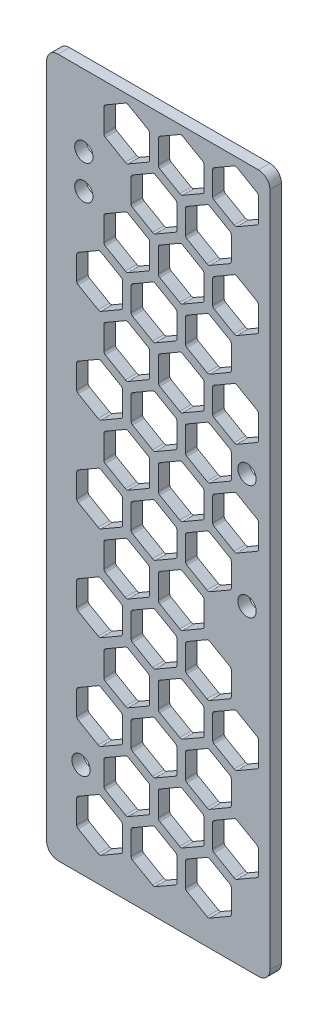
SolidWorks part; units mm, degrees
material "Thornel Mat VMA"
ref_plane "前视基准面" through (0, 0, 0) normal (0, 0, 1) x (1, 0, 0)
ref_plane "上视基准面" through (0, 0, 0) normal (0, 1, 0) x (1, 0, 0)
ref_plane "右视基准面" through (0, 0, 0) normal (1, 0, 0) x (0, 0, -1)
sketch "草图1" plane through (0, 0, 0) normal (0, 0, 1) x (1, 0, 0)
  line L0 (3, -11.5) -> (3, -16.5)
  line L1 (3, -16.5) -> (42, -16.5)
  line L3 (42, 105.5) -> (3, 105.5)
  line L4 (3, 105.5) -> (3, -11.5)
  line L5 (42, 105.5) -> (42, 80.5)
  line L6 (42, 80.5) -> (47, 80.5)
  line L7 (47, 80.5) -> (47, 72.5)
  line L8 (47, 72.5) -> (42, 72.5)
  line L9 (42, 72.5) -> (42, 16.5)
  line L10 (42, 16.5) -> (47, 16.5)
  line L11 (47, 16.5) -> (47, 8.5)
  line L12 (47, 8.5) -> (42, 8.5)
  line L13 (42, 8.5) -> (42, -16.5)
  circle A0 centre (9, 0) radius 1.6
  circle A1 centre (9.5, 93) radius 1.6
  circle A2 centre (9.5, 87) radius 1.6
  circle A3 centre (38, 38.5) radius 1.6
  circle A4 centre (38, 58.5) radius 1.6
  circle A5 centre (38, 58.5) radius 1.6 construction
  dimension "D1" = 25
  dimension "D10" = 20
  dimension "D2" = 8
  dimension "D3" = 5
  dimension "D4" = 8
  dimension "D5" = 5
  dimension "D6" = 25
  dimension "D8" = 5
extrude "凸台-拉伸1" add sketch "草图1" along normal blind 2
sketch "草图3" plane through (0, 0, 2) normal (0, 0, 1) x (1, 0, 0)
  line L0 (42, 80.5) -> (42, 72.5)
  line L1 (42, 72.5) -> (55.038, 72.5)
  line L2 (55.038, 72.5) -> (55.038, 80.5)
  line L3 (55.038, 80.5) -> (42, 80.5)
  line L4 (42, 16.5) -> (42, 8.5)
  line L5 (42, 8.5) -> (56.361, 8.5)
  line L6 (56.361, 8.5) -> (56.361, 16.5)
  line L7 (56.361, 16.5) -> (42, 16.5)
extrude "切除-拉伸2" cut sketch "草图3" against normal through all
sketch "草图4" plane through (0, 0, 2) normal (0, 0, 1) x (1, 0, 0)
  line L0 (42, -16.5) -> (42, 105.5) construction
  line L1 (35.75, 103.9745) -> (32.25, 101.9537)
  line L2 (32, 101.5207) -> (32, 97.4793)
  line L3 (32.25, 97.0463) -> (35.75, 95.0255)
  line L4 (36.25, 95.0255) -> (39.75, 97.0463)
  line L5 (40, 97.4793) -> (40, 101.5207)
  line L6 (39.75, 101.9537) -> (36.25, 103.9745)
  line L7 (42, 105.5) -> (3, 105.5) construction
  line L44 (26.25, 103.9745) -> (22.75, 101.9537)
  line L51 (22.5, 101.5207) -> (22.5, 97.4793)
  line L52 (22.75, 97.0463) -> (26.25, 95.0255)
  line L53 (26.75, 95.0255) -> (30.25, 97.0463)
  line L54 (30.5, 97.4793) -> (30.5, 101.5207)
  line L55 (30.25, 101.9537) -> (26.75, 103.9745)
  line L56 (16.75, 103.9745) -> (13.25, 101.9537)
  line L57 (13, 101.5207) -> (13, 97.4793)
  line L58 (13.25, 97.0463) -> (16.75, 95.0255)
  line L59 (17.25, 95.0255) -> (20.75, 97.0463)
  line L60 (21, 97.4793) -> (21, 101.5207)
  line L61 (20.75, 101.9537) -> (17.25, 103.9745)
  line L62 (21.5, 95.7472) -> (18, 93.7265)
  line L63 (31, 95.7472) -> (27.5, 93.7265)
  line L64 (27.25, 93.2935) -> (27.25, 89.252)
  line L65 (27.5, 88.819) -> (31, 86.7983)
  line L66 (31.5, 86.7983) -> (35, 88.819)
  line L67 (35.25, 89.252) -> (35.25, 93.2935)
  line L68 (35, 93.7265) -> (31.5, 95.7472)
  line L69 (17.75, 93.2935) -> (17.75, 89.252)
  line L70 (18, 88.819) -> (21.5, 86.7983)
  line L71 (22, 86.7983) -> (25.5, 88.819)
  line L72 (25.75, 89.252) -> (25.75, 93.2935)
  line L73 (25.5, 93.7265) -> (22, 95.7472)
  line L74 (26.25, 87.52) -> (22.75, 85.4993)
  line L75 (35.75, 87.52) -> (32.25, 85.4993)
  line L76 (32, 85.0662) -> (32, 81.0248)
  line L77 (32.25, 80.5918) -> (35.75, 78.5711)
  line L78 (36.25, 78.5711) -> (39.75, 80.5918)
  line L79 (40, 81.0248) -> (40, 85.0662)
  line L80 (39.75, 85.4993) -> (36.25, 87.52)
  line L81 (22.5, 85.0662) -> (22.5, 81.0248)
  line L82 (22.75, 80.5918) -> (26.25, 78.5711)
  line L83 (26.75, 78.5711) -> (30.25, 80.5918)
  line L84 (30.5, 81.0248) -> (30.5, 85.0662)
  line L85 (30.25, 85.4993) -> (26.75, 87.52)
  line L86 (16.75, 87.52) -> (13.25, 85.4993)
  line L87 (13, 85.0662) -> (13, 81.0248)
  line L88 (13.25, 80.5918) -> (16.75, 78.5711)
  line L89 (17.25, 78.5711) -> (20.75, 80.5918)
  line L90 (21, 81.0248) -> (21, 85.0662)
  line L91 (20.75, 85.4993) -> (17.25, 87.52)
  line L92 (21.5, 79.2927) -> (18, 77.272)
  line L93 (31, 79.2927) -> (27.5, 77.272)
  line L94 (27.25, 76.839) -> (27.25, 72.7976)
  line L95 (27.5, 72.3645) -> (31, 70.3438)
  line L96 (31.5, 70.3438) -> (35, 72.3645)
  line L97 (35.25, 72.7976) -> (35.25, 76.839)
  line L98 (35, 77.272) -> (31.5, 79.2927)
  line L99 (17.75, 76.839) -> (17.75, 72.7976)
  line L100 (18, 72.3645) -> (21.5, 70.3438)
  line L101 (22, 70.3438) -> (25.5, 72.3645)
  line L102 (25.75, 72.7976) -> (25.75, 76.839)
  line L103 (25.5, 77.272) -> (22, 79.2927)
  line L104 (12, 79.2927) -> (8.5, 77.272)
  line L105 (8.25, 76.839) -> (8.25, 72.7976)
  line L106 (8.5, 72.3645) -> (12, 70.3438)
  line L107 (12.5, 70.3438) -> (16, 72.3645)
  line L108 (16.25, 72.7976) -> (16.25, 76.839)
  line L109 (16, 77.272) -> (12.5, 79.2927)
  line L110 (16.75, 71.0655) -> (13.25, 69.0448)
  line L111 (13, 68.6118) -> (13, 64.5703)
  line L112 (13.25, 64.1373) -> (16.75, 62.1166)
  line L113 (17.25, 62.1166) -> (20.75, 64.1373)
  line L114 (21, 64.5703) -> (21, 68.6118)
  line L115 (20.75, 69.0448) -> (17.25, 71.0655)
  line L116 (26.25, 71.0655) -> (22.75, 69.0448)
  line L117 (22.5, 68.6118) -> (22.5, 64.5703)
  line L118 (22.75, 64.1373) -> (26.25, 62.1166)
  line L119 (26.75, 62.1166) -> (30.25, 64.1373)
  line L120 (30.5, 64.5703) -> (30.5, 68.6118)
  line L121 (30.25, 69.0448) -> (26.75, 71.0655)
  line L122 (35.75, 71.0655) -> (32.25, 69.0448)
  line L123 (32, 68.6118) -> (32, 64.5703)
  line L124 (32.25, 64.1373) -> (35.75, 62.1166)
  line L125 (36.25, 62.1166) -> (39.75, 64.1373)
  line L126 (40, 64.5703) -> (40, 68.6118)
  line L127 (39.75, 69.0448) -> (36.25, 71.0655)
  line L128 (31, 62.8383) -> (27.5, 60.8175)
  line L129 (27.25, 60.3845) -> (27.25, 56.3431)
  line L130 (27.5, 55.9101) -> (31, 53.8893)
  line L131 (31.5, 53.8893) -> (35, 55.9101)
  line L132 (35.25, 56.3431) -> (35.25, 60.3845)
  line L133 (35, 60.8175) -> (31.5, 62.8383)
  line L134 (21.5, 62.8383) -> (18, 60.8175)
  line L135 (17.75, 60.3845) -> (17.75, 56.3431)
  line L136 (18, 55.9101) -> (21.5, 53.8893)
  line L137 (22, 53.8893) -> (25.5, 55.9101)
  line L138 (25.75, 56.3431) -> (25.75, 60.3845)
  line L139 (25.5, 60.8175) -> (22, 62.8383)
  line L140 (12, 62.8383) -> (8.5, 60.8175)
  line L141 (8.25, 60.3845) -> (8.25, 56.3431)
  line L142 (8.5, 55.9101) -> (12, 53.8893)
  line L143 (12.5, 53.8893) -> (16, 55.9101)
  line L144 (16.25, 56.3431) -> (16.25, 60.3845)
  line L145 (16, 60.8175) -> (12.5, 62.8383)
  line L146 (16.75, 54.611) -> (13.25, 52.5903)
  line L147 (13, 52.1573) -> (13, 48.1158)
  line L148 (13.25, 47.6828) -> (16.75, 45.6621)
  line L149 (17.25, 45.6621) -> (20.75, 47.6828)
  line L150 (21, 48.1158) -> (21, 52.1573)
  line L151 (20.75, 52.5903) -> (17.25, 54.611)
  line L152 (26.25, 54.611) -> (22.75, 52.5903)
  line L153 (22.5, 52.1573) -> (22.5, 48.1158)
  line L154 (22.75, 47.6828) -> (26.25, 45.6621)
  line L155 (26.75, 45.6621) -> (30.25, 47.6828)
  line L156 (30.5, 48.1158) -> (30.5, 52.1573)
  line L157 (30.25, 52.5903) -> (26.75, 54.611)
  line L158 (35.75, 54.611) -> (32.25, 52.5903)
  line L159 (32, 52.1573) -> (32, 48.1158)
  line L160 (32.25, 47.6828) -> (35.75, 45.6621)
  line L161 (36.25, 45.6621) -> (39.75, 47.6828)
  line L162 (40, 48.1158) -> (40, 52.1573)
  line L163 (39.75, 52.5903) -> (36.25, 54.611)
  line L164 (31, 46.3838) -> (27.5, 44.363)
  line L165 (27.25, 43.93) -> (27.25, 39.8886)
  line L166 (27.5, 39.4556) -> (31, 37.4348)
  line L167 (31.5, 37.4348) -> (35, 39.4556)
  line L168 (35.25, 39.8886) -> (35.25, 43.93)
  line L169 (35, 44.363) -> (31.5, 46.3838)
  line L170 (21.5, 46.3838) -> (18, 44.363)
  line L171 (17.75, 43.93) -> (17.75, 39.8886)
  line L172 (18, 39.4556) -> (21.5, 37.4348)
  line L173 (22, 37.4348) -> (25.5, 39.4556)
  line L174 (25.75, 39.8886) -> (25.75, 43.93)
  line L175 (25.5, 44.363) -> (22, 46.3838)
  line L176 (12, 46.3838) -> (8.5, 44.363)
  line L177 (8.25, 43.93) -> (8.25, 39.8886)
  line L178 (8.5, 39.4556) -> (12, 37.4348)
  line L179 (12.5, 37.4348) -> (16, 39.4556)
  line L180 (16.25, 39.8886) -> (16.25, 43.93)
  line L181 (16, 44.363) -> (12.5, 46.3838)
  line L182 (16.75, 38.1565) -> (13.25, 36.1358)
  line L183 (13, 35.7028) -> (13, 31.6613)
  line L184 (13.25, 31.2283) -> (16.75, 29.2076)
  line L185 (17.25, 29.2076) -> (20.75, 31.2283)
  line L186 (21, 31.6613) -> (21, 35.7028)
  line L187 (20.75, 36.1358) -> (17.25, 38.1565)
  line L188 (26.25, 38.1565) -> (22.75, 36.1358)
  line L189 (22.5, 35.7028) -> (22.5, 31.6613)
  line L190 (22.75, 31.2283) -> (26.25, 29.2076)
  line L191 (26.75, 29.2076) -> (30.25, 31.2283)
  line L192 (30.5, 31.6613) -> (30.5, 35.7028)
  line L193 (30.25, 36.1358) -> (26.75, 38.1565)
  line L200 (31, 29.9293) -> (27.5, 27.9086)
  line L201 (27.25, 27.4756) -> (27.25, 23.4341)
  line L202 (27.5, 23.0011) -> (31, 20.9804)
  line L203 (31.5, 20.9804) -> (35, 23.0011)
  line L204 (35.25, 23.4341) -> (35.25, 27.4756)
  line L205 (35, 27.9086) -> (31.5, 29.9293)
  line L206 (21.5, 29.9293) -> (18, 27.9086)
  line L207 (17.75, 27.4756) -> (17.75, 23.4341)
  line L208 (18, 23.0011) -> (21.5, 20.9804)
  line L209 (22, 20.9804) -> (25.5, 23.0011)
  line L210 (25.75, 23.4341) -> (25.75, 27.4756)
  line L211 (25.5, 27.9086) -> (22, 29.9293)
  line L212 (12, 29.9293) -> (8.5, 27.9086)
  line L213 (8.25, 27.4756) -> (8.25, 23.4341)
  line L214 (8.5, 23.0011) -> (12, 20.9804)
  line L215 (12.5, 20.9804) -> (16, 23.0011)
  line L216 (16.25, 23.4341) -> (16.25, 27.4756)
  line L217 (16, 27.9086) -> (12.5, 29.9293)
  line L218 (16.75, 21.7021) -> (13.25, 19.6813)
  line L219 (13, 19.2483) -> (13, 15.2069)
  line L220 (13.25, 14.7738) -> (16.75, 12.7531)
  line L221 (17.25, 12.7531) -> (20.75, 14.7738)
  line L222 (21, 15.2069) -> (21, 19.2483)
  line L223 (20.75, 19.6813) -> (17.25, 21.7021)
  line L224 (26.25, 21.7021) -> (22.75, 19.6813)
  line L225 (22.5, 19.2483) -> (22.5, 15.2069)
  line L226 (22.75, 14.7738) -> (26.25, 12.7531)
  line L227 (26.75, 12.7531) -> (30.25, 14.7738)
  line L228 (30.5, 15.2069) -> (30.5, 19.2483)
  line L229 (30.25, 19.6813) -> (26.75, 21.7021)
  line L230 (35.75, 21.7021) -> (32.25, 19.6813)
  line L231 (32, 19.2483) -> (32, 15.2069)
  line L232 (32.25, 14.7738) -> (35.75, 12.7531)
  line L233 (36.25, 12.7531) -> (39.75, 14.7738)
  line L234 (40, 15.2069) -> (40, 19.2483)
  line L235 (39.75, 19.6813) -> (36.25, 21.7021)
  line L236 (31, 13.4748) -> (27.5, 11.4541)
  line L237 (27.25, 11.0211) -> (27.25, 6.9796)
  line L238 (27.5, 6.5466) -> (31, 4.5259)
  line L239 (31.5, 4.5259) -> (35, 6.5466)
  line L240 (35.25, 6.9796) -> (35.25, 11.0211)
  line L241 (35, 11.4541) -> (31.5, 13.4748)
  line L242 (21.5, 13.4748) -> (18, 11.4541)
  line L243 (17.75, 11.0211) -> (17.75, 6.9796)
  line L244 (18, 6.5466) -> (21.5, 4.5259)
  line L245 (22, 4.5259) -> (25.5, 6.5466)
  line L246 (25.75, 6.9796) -> (25.75, 11.0211)
  line L247 (25.5, 11.4541) -> (22, 13.4748)
  line L248 (12, 13.4748) -> (8.5, 11.4541)
  line L249 (8.25, 11.0211) -> (8.25, 6.9796)
  line L250 (8.5, 6.5466) -> (12, 4.5259)
  line L251 (12.5, 4.5259) -> (16, 6.5466)
  line L252 (16.25, 6.9796) -> (16.25, 11.0211)
  line L253 (16, 11.4541) -> (12.5, 13.4748)
  line L254 (16.75, 5.2476) -> (13.25, 3.2268)
  line L255 (13, 2.7938) -> (13, -1.2476)
  line L256 (13.25, -1.6806) -> (16.75, -3.7014)
  line L257 (17.25, -3.7014) -> (20.75, -1.6806)
  line L258 (21, -1.2476) -> (21, 2.7938)
  line L259 (20.75, 3.2268) -> (17.25, 5.2476)
  line L260 (26.25, 5.2476) -> (22.75, 3.2268)
  line L261 (22.5, 2.7938) -> (22.5, -1.2476)
  line L262 (22.75, -1.6806) -> (26.25, -3.7014)
  line L263 (26.75, -3.7014) -> (30.25, -1.6806)
  line L264 (30.5, -1.2476) -> (30.5, 2.7938)
  line L265 (30.25, 3.2268) -> (26.75, 5.2476)
  line L266 (35.75, 5.2476) -> (32.25, 3.2268)
  line L267 (32, 2.7938) -> (32, -1.2476)
  line L268 (32.25, -1.6806) -> (35.75, -3.7014)
  line L269 (36.25, -3.7014) -> (39.75, -1.6806)
  line L270 (40, -1.2476) -> (40, 2.7938)
  line L271 (39.75, 3.2268) -> (36.25, 5.2476)
  line L272 (31, -2.9797) -> (27.5, -5.0004)
  line L273 (27.25, -5.4334) -> (27.25, -9.4749)
  line L274 (27.5, -9.9079) -> (31, -11.9286)
  line L275 (31.5, -11.9286) -> (35, -9.9079)
  line L276 (35.25, -9.4749) -> (35.25, -5.4334)
  line L277 (35, -5.0004) -> (31.5, -2.9797)
  line L278 (21.5, -2.9797) -> (18, -5.0004)
  line L279 (17.75, -5.4334) -> (17.75, -9.4749)
  line L280 (18, -9.9079) -> (21.5, -11.9286)
  line L281 (22, -11.9286) -> (25.5, -9.9079)
  line L282 (25.75, -9.4749) -> (25.75, -5.4334)
  line L283 (25.5, -5.0004) -> (22, -2.9797)
  line L284 (12, -2.9797) -> (8.5, -5.0004)
  line L285 (8.25, -5.4334) -> (8.25, -9.4749)
  line L286 (8.5, -9.9079) -> (12, -11.9286)
  line L287 (12.5, -11.9286) -> (16, -9.9079)
  line L288 (16.25, -9.4749) -> (16.25, -5.4334)
  line L289 (16, -5.0004) -> (12.5, -2.9797)
  line L290 (35.75, 38.1565) -> (32.25, 36.1358) [skipped]
  line L291 (32, 35.7028) -> (32, 31.6613) [skipped]
  line L292 (32.25, 31.2283) -> (35.75, 29.2076) [skipped]
  line L293 (36.25, 29.2076) -> (39.75, 31.2283) [skipped]
  line L294 (40, 31.6613) -> (40, 35.7028) [skipped]
  line L295 (39.75, 36.1358) -> (36.25, 38.1565) [skipped]
  circle A0 centre (36, 99.5) radius 4 construction
  arc A1 (32.25, 101.9537) -> (32, 101.5207) centre (32.5, 101.5207) ccw
  arc A2 (32, 97.4793) -> (32.25, 97.0463) centre (32.5, 97.4793) ccw
  arc A3 (35.75, 95.0255) -> (36.25, 95.0255) centre (36, 95.4585) ccw
  arc A4 (39.75, 97.0463) -> (40, 97.4793) centre (39.5, 97.4793) ccw
  arc A5 (40, 101.5207) -> (39.75, 101.9537) centre (39.5, 101.5207) ccw
  arc A6 (35.75, 103.9745) -> (36.25, 103.9745) centre (36, 103.5415) cw
  arc A45 (22.75, 101.9537) -> (22.5, 101.5207) centre (23, 101.5207) ccw
  arc A46 (22.5, 97.4793) -> (22.75, 97.0463) centre (23, 97.4793) ccw
  arc A47 (26.25, 95.0255) -> (26.75, 95.0255) centre (26.5, 95.4585) ccw
  arc A48 (30.25, 97.0463) -> (30.5, 97.4793) centre (30, 97.4793) ccw
  arc A49 (30.5, 101.5207) -> (30.25, 101.9537) centre (30, 101.5207) ccw
  arc A50 (26.25, 103.9745) -> (26.75, 103.9745) centre (26.5, 103.5415) cw
  circle A51 centre (26.5, 99.5) radius 4 construction
  arc A52 (13.25, 101.9537) -> (13, 101.5207) centre (13.5, 101.5207) ccw
  arc A53 (13, 97.4793) -> (13.25, 97.0463) centre (13.5, 97.4793) ccw
  arc A54 (16.75, 95.0255) -> (17.25, 95.0255) centre (17, 95.4585) ccw
  arc A55 (20.75, 97.0463) -> (21, 97.4793) centre (20.5, 97.4793) ccw
  arc A56 (21, 101.5207) -> (20.75, 101.9537) centre (20.5, 101.5207) ccw
  arc A57 (16.75, 103.9745) -> (17.25, 103.9745) centre (17, 103.5415) cw
  circle A58 centre (17, 99.5) radius 4 construction
  circle A59 centre (31.25, 91.2728) radius 4 construction
  arc A60 (27.5, 93.7265) -> (27.25, 93.2935) centre (27.75, 93.2935) ccw
  arc A61 (27.25, 89.252) -> (27.5, 88.819) centre (27.75, 89.252) ccw
  arc A62 (31, 86.7983) -> (31.5, 86.7983) centre (31.25, 87.2313) ccw
  arc A63 (35, 88.819) -> (35.25, 89.252) centre (34.75, 89.252) ccw
  arc A64 (35.25, 93.2935) -> (35, 93.7265) centre (34.75, 93.2935) ccw
  arc A65 (31, 95.7472) -> (31.5, 95.7472) centre (31.25, 95.3142) cw
  arc A66 (21.5, 95.7472) -> (22, 95.7472) centre (21.75, 95.3142) cw
  arc A67 (18, 93.7265) -> (17.75, 93.2935) centre (18.25, 93.2935) ccw
  arc A68 (17.75, 89.252) -> (18, 88.819) centre (18.25, 89.252) ccw
  arc A69 (21.5, 86.7983) -> (22, 86.7983) centre (21.75, 87.2313) ccw
  arc A70 (25.5, 88.819) -> (25.75, 89.252) centre (25.25, 89.252) ccw
  arc A71 (25.75, 93.2935) -> (25.5, 93.7265) centre (25.25, 93.2935) ccw
  circle A72 centre (36, 83.0455) radius 4 construction
  arc A73 (32.25, 85.4993) -> (32, 85.0662) centre (32.5, 85.0662) ccw
  arc A74 (32, 81.0248) -> (32.25, 80.5918) centre (32.5, 81.0248) ccw
  arc A75 (35.75, 78.5711) -> (36.25, 78.5711) centre (36, 79.0041) ccw
  arc A76 (39.75, 80.5918) -> (40, 81.0248) centre (39.5, 81.0248) ccw
  arc A77 (40, 85.0662) -> (39.75, 85.4993) centre (39.5, 85.0662) ccw
  arc A78 (35.75, 87.52) -> (36.25, 87.52) centre (36, 87.087) cw
  arc A79 (26.25, 87.52) -> (26.75, 87.52) centre (26.5, 87.087) cw
  arc A80 (22.75, 85.4993) -> (22.5, 85.0662) centre (23, 85.0662) ccw
  arc A81 (22.5, 81.0248) -> (22.75, 80.5918) centre (23, 81.0248) ccw
  arc A82 (26.25, 78.5711) -> (26.75, 78.5711) centre (26.5, 79.0041) ccw
  arc A83 (30.25, 80.5918) -> (30.5, 81.0248) centre (30, 81.0248) ccw
  arc A84 (30.5, 85.0662) -> (30.25, 85.4993) centre (30, 85.0662) ccw
  arc A85 (16.75, 87.52) -> (17.25, 87.52) centre (17, 87.087) cw
  arc A86 (13.25, 85.4993) -> (13, 85.0662) centre (13.5, 85.0662) ccw
  arc A87 (13, 81.0248) -> (13.25, 80.5918) centre (13.5, 81.0248) ccw
  arc A88 (16.75, 78.5711) -> (17.25, 78.5711) centre (17, 79.0041) ccw
  arc A89 (20.75, 80.5918) -> (21, 81.0248) centre (20.5, 81.0248) ccw
  arc A90 (21, 85.0662) -> (20.75, 85.4993) centre (20.5, 85.0662) ccw
  circle A91 centre (31.25, 74.8183) radius 4 construction
  arc A92 (27.5, 77.272) -> (27.25, 76.839) centre (27.75, 76.839) ccw
  arc A93 (27.25, 72.7976) -> (27.5, 72.3645) centre (27.75, 72.7976) ccw
  arc A94 (31, 70.3438) -> (31.5, 70.3438) centre (31.25, 70.7768) ccw
  arc A95 (35, 72.3645) -> (35.25, 72.7976) centre (34.75, 72.7976) ccw
  arc A96 (35.25, 76.839) -> (35, 77.272) centre (34.75, 76.839) ccw
  arc A97 (31, 79.2927) -> (31.5, 79.2927) centre (31.25, 78.8597) cw
  arc A98 (21.5, 79.2927) -> (22, 79.2927) centre (21.75, 78.8597) cw
  arc A99 (18, 77.272) -> (17.75, 76.839) centre (18.25, 76.839) ccw
  arc A100 (17.75, 72.7976) -> (18, 72.3645) centre (18.25, 72.7976) ccw
  arc A101 (21.5, 70.3438) -> (22, 70.3438) centre (21.75, 70.7768) ccw
  arc A102 (25.5, 72.3645) -> (25.75, 72.7976) centre (25.25, 72.7976) ccw
  arc A103 (25.75, 76.839) -> (25.5, 77.272) centre (25.25, 76.839) ccw
  arc A104 (12, 79.2927) -> (12.5, 79.2927) centre (12.25, 78.8597) cw
  arc A105 (8.5, 77.272) -> (8.25, 76.839) centre (8.75, 76.839) ccw
  arc A106 (8.25, 72.7976) -> (8.5, 72.3645) centre (8.75, 72.7976) ccw
  arc A107 (12, 70.3438) -> (12.5, 70.3438) centre (12.25, 70.7768) ccw
  arc A108 (16, 72.3645) -> (16.25, 72.7976) centre (15.75, 72.7976) ccw
  arc A109 (16.25, 76.839) -> (16, 77.272) centre (15.75, 76.839) ccw
  arc A110 (13.25, 69.0448) -> (13, 68.6118) centre (13.5, 68.6118) ccw
  arc A111 (13, 64.5703) -> (13.25, 64.1373) centre (13.5, 64.5703) ccw
  arc A112 (16.75, 62.1166) -> (17.25, 62.1166) centre (17, 62.5496) ccw
  arc A113 (20.75, 64.1373) -> (21, 64.5703) centre (20.5, 64.5703) ccw
  arc A114 (21, 68.6118) -> (20.75, 69.0448) centre (20.5, 68.6118) ccw
  arc A115 (16.75, 71.0655) -> (17.25, 71.0655) centre (17, 70.6325) cw
  arc A116 (22.75, 69.0448) -> (22.5, 68.6118) centre (23, 68.6118) ccw
  arc A117 (22.5, 64.5703) -> (22.75, 64.1373) centre (23, 64.5703) ccw
  arc A118 (26.25, 62.1166) -> (26.75, 62.1166) centre (26.5, 62.5496) ccw
  arc A119 (30.25, 64.1373) -> (30.5, 64.5703) centre (30, 64.5703) ccw
  arc A120 (30.5, 68.6118) -> (30.25, 69.0448) centre (30, 68.6118) ccw
  arc A121 (26.25, 71.0655) -> (26.75, 71.0655) centre (26.5, 70.6325) cw
  arc A122 (35.75, 71.0655) -> (36.25, 71.0655) centre (36, 70.6325) cw
  arc A123 (32.25, 69.0448) -> (32, 68.6118) centre (32.5, 68.6118) ccw
  arc A124 (32, 64.5703) -> (32.25, 64.1373) centre (32.5, 64.5703) ccw
  arc A125 (35.75, 62.1166) -> (36.25, 62.1166) centre (36, 62.5496) ccw
  arc A126 (39.75, 64.1373) -> (40, 64.5703) centre (39.5, 64.5703) ccw
  arc A127 (40, 68.6118) -> (39.75, 69.0448) centre (39.5, 68.6118) ccw
  arc A128 (31, 62.8383) -> (31.5, 62.8383) centre (31.25, 62.4052) cw
  arc A129 (27.5, 60.8175) -> (27.25, 60.3845) centre (27.75, 60.3845) ccw
  arc A130 (27.25, 56.3431) -> (27.5, 55.9101) centre (27.75, 56.3431) ccw
  arc A131 (31, 53.8893) -> (31.5, 53.8893) centre (31.25, 54.3223) ccw
  arc A132 (35, 55.9101) -> (35.25, 56.3431) centre (34.75, 56.3431) ccw
  arc A133 (35.25, 60.3845) -> (35, 60.8175) centre (34.75, 60.3845) ccw
  arc A134 (18, 60.8175) -> (17.75, 60.3845) centre (18.25, 60.3845) ccw
  arc A135 (17.75, 56.3431) -> (18, 55.9101) centre (18.25, 56.3431) ccw
  arc A136 (21.5, 53.8893) -> (22, 53.8893) centre (21.75, 54.3223) ccw
  arc A137 (25.5, 55.9101) -> (25.75, 56.3431) centre (25.25, 56.3431) ccw
  arc A138 (25.75, 60.3845) -> (25.5, 60.8175) centre (25.25, 60.3845) ccw
  arc A139 (21.5, 62.8383) -> (22, 62.8383) centre (21.75, 62.4052) cw
  arc A140 (8.5, 60.8175) -> (8.25, 60.3845) centre (8.75, 60.3845) ccw
  arc A141 (8.25, 56.3431) -> (8.5, 55.9101) centre (8.75, 56.3431) ccw
  arc A142 (12, 53.8893) -> (12.5, 53.8893) centre (12.25, 54.3223) ccw
  arc A143 (16, 55.9101) -> (16.25, 56.3431) centre (15.75, 56.3431) ccw
  arc A144 (16.25, 60.3845) -> (16, 60.8175) centre (15.75, 60.3845) ccw
  arc A145 (12, 62.8383) -> (12.5, 62.8383) centre (12.25, 62.4052) cw
  arc A146 (13.25, 52.5903) -> (13, 52.1573) centre (13.5, 52.1573) ccw
  arc A147 (13, 48.1158) -> (13.25, 47.6828) centre (13.5, 48.1158) ccw
  arc A148 (16.75, 45.6621) -> (17.25, 45.6621) centre (17, 46.0951) ccw
  arc A149 (20.75, 47.6828) -> (21, 48.1158) centre (20.5, 48.1158) ccw
  arc A150 (21, 52.1573) -> (20.75, 52.5903) centre (20.5, 52.1573) ccw
  arc A151 (16.75, 54.611) -> (17.25, 54.611) centre (17, 54.178) cw
  arc A152 (22.75, 52.5903) -> (22.5, 52.1573) centre (23, 52.1573) ccw
  arc A153 (22.5, 48.1158) -> (22.75, 47.6828) centre (23, 48.1158) ccw
  arc A154 (26.25, 45.6621) -> (26.75, 45.6621) centre (26.5, 46.0951) ccw
  arc A155 (30.25, 47.6828) -> (30.5, 48.1158) centre (30, 48.1158) ccw
  arc A156 (30.5, 52.1573) -> (30.25, 52.5903) centre (30, 52.1573) ccw
  arc A157 (26.25, 54.611) -> (26.75, 54.611) centre (26.5, 54.178) cw
  arc A158 (32.25, 52.5903) -> (32, 52.1573) centre (32.5, 52.1573) ccw
  arc A159 (32, 48.1158) -> (32.25, 47.6828) centre (32.5, 48.1158) ccw
  arc A160 (35.75, 45.6621) -> (36.25, 45.6621) centre (36, 46.0951) ccw
  arc A161 (39.75, 47.6828) -> (40, 48.1158) centre (39.5, 48.1158) ccw
  arc A162 (40, 52.1573) -> (39.75, 52.5903) centre (39.5, 52.1573) ccw
  arc A163 (35.75, 54.611) -> (36.25, 54.611) centre (36, 54.178) cw
  arc A164 (27.5, 44.363) -> (27.25, 43.93) centre (27.75, 43.93) ccw
  arc A165 (27.25, 39.8886) -> (27.5, 39.4556) centre (27.75, 39.8886) ccw
  arc A166 (31, 37.4348) -> (31.5, 37.4348) centre (31.25, 37.8679) ccw
  arc A167 (35, 39.4556) -> (35.25, 39.8886) centre (34.75, 39.8886) ccw
  arc A168 (35.25, 43.93) -> (35, 44.363) centre (34.75, 43.93) ccw
  arc A169 (31, 46.3838) -> (31.5, 46.3838) centre (31.25, 45.9508) cw
  arc A170 (18, 44.363) -> (17.75, 43.93) centre (18.25, 43.93) ccw
  arc A171 (17.75, 39.8886) -> (18, 39.4556) centre (18.25, 39.8886) ccw
  arc A172 (21.5, 37.4348) -> (22, 37.4348) centre (21.75, 37.8679) ccw
  arc A173 (25.5, 39.4556) -> (25.75, 39.8886) centre (25.25, 39.8886) ccw
  arc A174 (25.75, 43.93) -> (25.5, 44.363) centre (25.25, 43.93) ccw
  arc A175 (21.5, 46.3838) -> (22, 46.3838) centre (21.75, 45.9508) cw
  arc A176 (8.5, 44.363) -> (8.25, 43.93) centre (8.75, 43.93) ccw
  arc A177 (8.25, 39.8886) -> (8.5, 39.4556) centre (8.75, 39.8886) ccw
  arc A178 (12, 37.4348) -> (12.5, 37.4348) centre (12.25, 37.8679) ccw
  arc A179 (16, 39.4556) -> (16.25, 39.8886) centre (15.75, 39.8886) ccw
  arc A180 (16.25, 43.93) -> (16, 44.363) centre (15.75, 43.93) ccw
  arc A181 (12, 46.3838) -> (12.5, 46.3838) centre (12.25, 45.9508) cw
  arc A182 (13.25, 36.1358) -> (13, 35.7028) centre (13.5, 35.7028) ccw
  arc A183 (13, 31.6613) -> (13.25, 31.2283) centre (13.5, 31.6613) ccw
  arc A184 (16.75, 29.2076) -> (17.25, 29.2076) centre (17, 29.6406) ccw
  arc A185 (20.75, 31.2283) -> (21, 31.6613) centre (20.5, 31.6613) ccw
  arc A186 (21, 35.7028) -> (20.75, 36.1358) centre (20.5, 35.7028) ccw
  arc A187 (16.75, 38.1565) -> (17.25, 38.1565) centre (17, 37.7235) cw
  arc A188 (22.75, 36.1358) -> (22.5, 35.7028) centre (23, 35.7028) ccw
  arc A189 (22.5, 31.6613) -> (22.75, 31.2283) centre (23, 31.6613) ccw
  arc A190 (26.25, 29.2076) -> (26.75, 29.2076) centre (26.5, 29.6406) ccw
  arc A191 (30.25, 31.2283) -> (30.5, 31.6613) centre (30, 31.6613) ccw
  arc A192 (30.5, 35.7028) -> (30.25, 36.1358) centre (30, 35.7028) ccw
  arc A193 (26.25, 38.1565) -> (26.75, 38.1565) centre (26.5, 37.7235) cw
  arc A200 (27.5, 27.9086) -> (27.25, 27.4756) centre (27.75, 27.4756) ccw
  arc A201 (27.25, 23.4341) -> (27.5, 23.0011) centre (27.75, 23.4341) ccw
  arc A202 (31, 20.9804) -> (31.5, 20.9804) centre (31.25, 21.4134) ccw
  arc A203 (35, 23.0011) -> (35.25, 23.4341) centre (34.75, 23.4341) ccw
  arc A204 (35.25, 27.4756) -> (35, 27.9086) centre (34.75, 27.4756) ccw
  arc A205 (31, 29.9293) -> (31.5, 29.9293) centre (31.25, 29.4963) cw
  arc A206 (18, 27.9086) -> (17.75, 27.4756) centre (18.25, 27.4756) ccw
  arc A207 (17.75, 23.4341) -> (18, 23.0011) centre (18.25, 23.4341) ccw
  arc A208 (21.5, 20.9804) -> (22, 20.9804) centre (21.75, 21.4134) ccw
  arc A209 (25.5, 23.0011) -> (25.75, 23.4341) centre (25.25, 23.4341) ccw
  arc A210 (25.75, 27.4756) -> (25.5, 27.9086) centre (25.25, 27.4756) ccw
  arc A211 (21.5, 29.9293) -> (22, 29.9293) centre (21.75, 29.4963) cw
  arc A212 (8.5, 27.9086) -> (8.25, 27.4756) centre (8.75, 27.4756) ccw
  arc A213 (8.25, 23.4341) -> (8.5, 23.0011) centre (8.75, 23.4341) ccw
  arc A214 (12, 20.9804) -> (12.5, 20.9804) centre (12.25, 21.4134) ccw
  arc A215 (16, 23.0011) -> (16.25, 23.4341) centre (15.75, 23.4341) ccw
  arc A216 (16.25, 27.4756) -> (16, 27.9086) centre (15.75, 27.4756) ccw
  arc A217 (12, 29.9293) -> (12.5, 29.9293) centre (12.25, 29.4963) cw
  arc A218 (13.25, 19.6813) -> (13, 19.2483) centre (13.5, 19.2483) ccw
  arc A219 (13, 15.2069) -> (13.25, 14.7738) centre (13.5, 15.2069) ccw
  arc A220 (16.75, 12.7531) -> (17.25, 12.7531) centre (17, 13.1861) ccw
  arc A221 (20.75, 14.7738) -> (21, 15.2069) centre (20.5, 15.2069) ccw
  arc A222 (21, 19.2483) -> (20.75, 19.6813) centre (20.5, 19.2483) ccw
  arc A223 (16.75, 21.7021) -> (17.25, 21.7021) centre (17, 21.269) cw
  arc A224 (22.75, 19.6813) -> (22.5, 19.2483) centre (23, 19.2483) ccw
  arc A225 (22.5, 15.2069) -> (22.75, 14.7738) centre (23, 15.2069) ccw
  arc A226 (26.25, 12.7531) -> (26.75, 12.7531) centre (26.5, 13.1861) ccw
  arc A227 (30.25, 14.7738) -> (30.5, 15.2069) centre (30, 15.2069) ccw
  arc A228 (30.5, 19.2483) -> (30.25, 19.6813) centre (30, 19.2483) ccw
  arc A229 (26.25, 21.7021) -> (26.75, 21.7021) centre (26.5, 21.269) cw
  arc A230 (32.25, 19.6813) -> (32, 19.2483) centre (32.5, 19.2483) ccw
  arc A231 (32, 15.2069) -> (32.25, 14.7738) centre (32.5, 15.2069) ccw
  arc A232 (35.75, 12.7531) -> (36.25, 12.7531) centre (36, 13.1861) ccw
  arc A233 (39.75, 14.7738) -> (40, 15.2069) centre (39.5, 15.2069) ccw
  arc A234 (40, 19.2483) -> (39.75, 19.6813) centre (39.5, 19.2483) ccw
  arc A235 (35.75, 21.7021) -> (36.25, 21.7021) centre (36, 21.269) cw
  arc A236 (27.5, 11.4541) -> (27.25, 11.0211) centre (27.75, 11.0211) ccw
  arc A237 (27.25, 6.9796) -> (27.5, 6.5466) centre (27.75, 6.9796) ccw
  arc A238 (31, 4.5259) -> (31.5, 4.5259) centre (31.25, 4.9589) ccw
  arc A239 (35, 6.5466) -> (35.25, 6.9796) centre (34.75, 6.9796) ccw
  arc A240 (35.25, 11.0211) -> (35, 11.4541) centre (34.75, 11.0211) ccw
  arc A241 (31, 13.4748) -> (31.5, 13.4748) centre (31.25, 13.0418) cw
  arc A242 (18, 11.4541) -> (17.75, 11.0211) centre (18.25, 11.0211) ccw
  arc A243 (17.75, 6.9796) -> (18, 6.5466) centre (18.25, 6.9796) ccw
  arc A244 (21.5, 4.5259) -> (22, 4.5259) centre (21.75, 4.9589) ccw
  arc A245 (25.5, 6.5466) -> (25.75, 6.9796) centre (25.25, 6.9796) ccw
  arc A246 (25.75, 11.0211) -> (25.5, 11.4541) centre (25.25, 11.0211) ccw
  arc A247 (21.5, 13.4748) -> (22, 13.4748) centre (21.75, 13.0418) cw
  arc A248 (8.5, 11.4541) -> (8.25, 11.0211) centre (8.75, 11.0211) ccw
  arc A249 (8.25, 6.9796) -> (8.5, 6.5466) centre (8.75, 6.9796) ccw
  arc A250 (12, 4.5259) -> (12.5, 4.5259) centre (12.25, 4.9589) ccw
  arc A251 (16, 6.5466) -> (16.25, 6.9796) centre (15.75, 6.9796) ccw
  arc A252 (16.25, 11.0211) -> (16, 11.4541) centre (15.75, 11.0211) ccw
  arc A253 (12, 13.4748) -> (12.5, 13.4748) centre (12.25, 13.0418) cw
  arc A254 (13.25, 3.2268) -> (13, 2.7938) centre (13.5, 2.7938) ccw
  arc A255 (13, -1.2476) -> (13.25, -1.6806) centre (13.5, -1.2476) ccw
  arc A256 (16.75, -3.7014) -> (17.25, -3.7014) centre (17, -3.2683) ccw
  arc A257 (20.75, -1.6806) -> (21, -1.2476) centre (20.5, -1.2476) ccw
  arc A258 (21, 2.7938) -> (20.75, 3.2268) centre (20.5, 2.7938) ccw
  arc A259 (16.75, 5.2476) -> (17.25, 5.2476) centre (17, 4.8146) cw
  arc A260 (22.75, 3.2268) -> (22.5, 2.7938) centre (23, 2.7938) ccw
  arc A261 (22.5, -1.2476) -> (22.75, -1.6806) centre (23, -1.2476) ccw
  arc A262 (26.25, -3.7014) -> (26.75, -3.7014) centre (26.5, -3.2683) ccw
  arc A263 (30.25, -1.6806) -> (30.5, -1.2476) centre (30, -1.2476) ccw
  arc A264 (30.5, 2.7938) -> (30.25, 3.2268) centre (30, 2.7938) ccw
  arc A265 (26.25, 5.2476) -> (26.75, 5.2476) centre (26.5, 4.8146) cw
  arc A266 (32.25, 3.2268) -> (32, 2.7938) centre (32.5, 2.7938) ccw
  arc A267 (32, -1.2476) -> (32.25, -1.6806) centre (32.5, -1.2476) ccw
  arc A268 (35.75, -3.7014) -> (36.25, -3.7014) centre (36, -3.2683) ccw
  arc A269 (39.75, -1.6806) -> (40, -1.2476) centre (39.5, -1.2476) ccw
  arc A270 (40, 2.7938) -> (39.75, 3.2268) centre (39.5, 2.7938) ccw
  arc A271 (35.75, 5.2476) -> (36.25, 5.2476) centre (36, 4.8146) cw
  arc A272 (27.5, -5.0004) -> (27.25, -5.4334) centre (27.75, -5.4334) ccw
  arc A273 (27.25, -9.4749) -> (27.5, -9.9079) centre (27.75, -9.4749) ccw
  arc A274 (31, -11.9286) -> (31.5, -11.9286) centre (31.25, -11.4956) ccw
  arc A275 (35, -9.9079) -> (35.25, -9.4749) centre (34.75, -9.4749) ccw
  arc A276 (35.25, -5.4334) -> (35, -5.0004) centre (34.75, -5.4334) ccw
  arc A277 (31, -2.9797) -> (31.5, -2.9797) centre (31.25, -3.4127) cw
  arc A278 (18, -5.0004) -> (17.75, -5.4334) centre (18.25, -5.4334) ccw
  arc A279 (17.75, -9.4749) -> (18, -9.9079) centre (18.25, -9.4749) ccw
  arc A280 (21.5, -11.9286) -> (22, -11.9286) centre (21.75, -11.4956) ccw
  arc A281 (25.5, -9.9079) -> (25.75, -9.4749) centre (25.25, -9.4749) ccw
  arc A282 (25.75, -5.4334) -> (25.5, -5.0004) centre (25.25, -5.4334) ccw
  arc A283 (21.5, -2.9797) -> (22, -2.9797) centre (21.75, -3.4127) cw
  arc A284 (8.5, -5.0004) -> (8.25, -5.4334) centre (8.75, -5.4334) ccw
  arc A285 (8.25, -9.4749) -> (8.5, -9.9079) centre (8.75, -9.4749) ccw
  arc A286 (12, -11.9286) -> (12.5, -11.9286) centre (12.25, -11.4956) ccw
  arc A287 (16, -9.9079) -> (16.25, -9.4749) centre (15.75, -9.4749) ccw
  arc A288 (16.25, -5.4334) -> (16, -5.0004) centre (15.75, -5.4334) ccw
  arc A289 (12, -2.9797) -> (12.5, -2.9797) centre (12.25, -3.4127) cw
  arc A290 (32.25, 36.1358) -> (32, 35.7028) centre (32.5, 35.7028) ccw [skipped]
  arc A291 (32, 31.6613) -> (32.25, 31.2283) centre (32.5, 31.6613) ccw [skipped]
  arc A292 (35.75, 29.2076) -> (36.25, 29.2076) centre (36, 29.6406) ccw [skipped]
  arc A293 (39.75, 31.2283) -> (40, 31.6613) centre (39.5, 31.6613) ccw [skipped]
  arc A294 (40, 35.7028) -> (39.75, 36.1358) centre (39.5, 35.7028) ccw [skipped]
  arc A295 (35.75, 38.1565) -> (36.25, 38.1565) centre (36, 37.7235) cw [skipped]
  dimension "D1" = 8
  dimension "D4" = 0.5
  dimension "D5" = 3
  dimension "D6" = 9.5
  dimension "D7" = 8
  dimension "D10" = 0.5
  dimension "D13" = 8
  dimension "D14" = 0.5
  dimension "D18" = 8
  dimension "D19" = 0.5
  dimension "D2" = 6
  dimension "D3" = 6
  dimension "D8" = 1.5
  dimension "D9" = 1.5
  dimension "D12" = 1.5
  dimension "D15" = 1.5
  dimension "D16" = 6
  dimension "D20" = 1.5
  dimension "D21" = 1.5
  dimension "D22" = 1.5
  dimension "D24" = 1.5
  dimension "D26" = 1.5
  dimension "D28" = 1.5
  dimension "D11" = 2
  dimension "D17" = 3
  dimension "D23" = 3
  dimension "D25" = 2
  dimension "D27" = 5
extrude "切除-拉伸3" cut sketch "草图4" against normal through all
fillet "圆角1" radius 2 4 edges at (42, -16.5, 1) (3, -16.5, 1) (3, 105.5, 1) (42, 105.5, 1)
